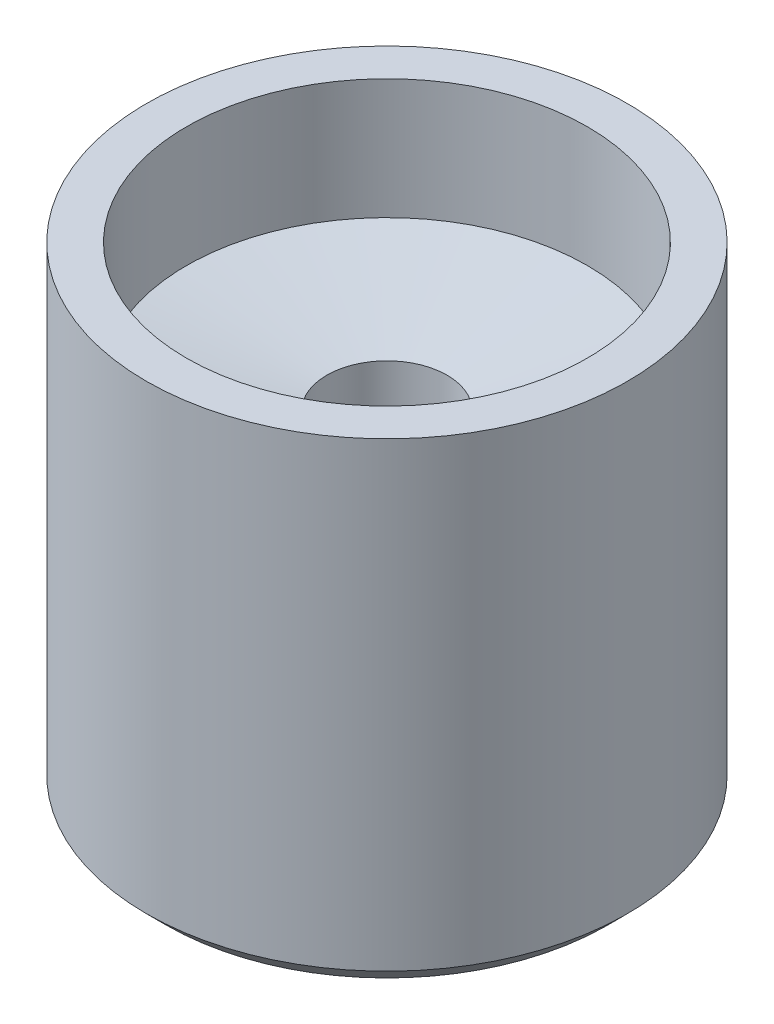
SolidWorks part; units mm, degrees
ref_plane "Front Plane" through (0, 0, 0) normal (0, 0, 1) x (1, 0, 0)
ref_plane "Top Plane" through (0, 0, 0) normal (0, 1, 0) x (1, 0, 0)
ref_plane "Right Plane" through (0, 0, 0) normal (1, 0, 0) x (0, 0, -1)
sketch "Sketch1" plane through (0, 0, 0) normal (0, 1, 0) x (1, 0, 0)
  circle A0 centre (0, 0) radius 6
  dimension "D1" = 12
extrude "Boss-Extrude1" add sketch "Sketch1" along normal blind 12
sketch "Sketch2" plane through (0, 12, 0) normal (0, 1, 0) x (1, 0, 0)
  circle A0 centre (0, 0) radius 5
  dimension "D1" = 10
extrude "Cut-Extrude1" cut sketch "Sketch2" against normal blind 3
sketch "Sketch3" plane through (0, 0, 0) normal (0, 0, 1) x (1, 0, 0)
  line L0 (-5, 9) -> (-1.5, 8.3829)
  line L1 (-1.5, 8.3829) -> (-1.5, 3.5)
  line L2 (5, 9) -> (-5, 9) construction
  line L3 (-5, 9) -> (-5, 12.1102) construction
  line L4 (5, 12) -> (-5, 12) construction
  line L5 (-1.5, 3.5) -> (0, 3.5)
  line L6 (0, 3.5) -> (0, 9)
  line L7 (0, 9) -> (-5, 9)
  dimension "D1" = 100
  dimension "D2" = 1.5
  dimension "D3" = 8.5
revolve "Cut-Revolve1" cut sketch "Sketch3" angle 360 about L6
chamfer "Chamfer1" distance 0.5 angle 45 1 edges at (0, 0, 6)
